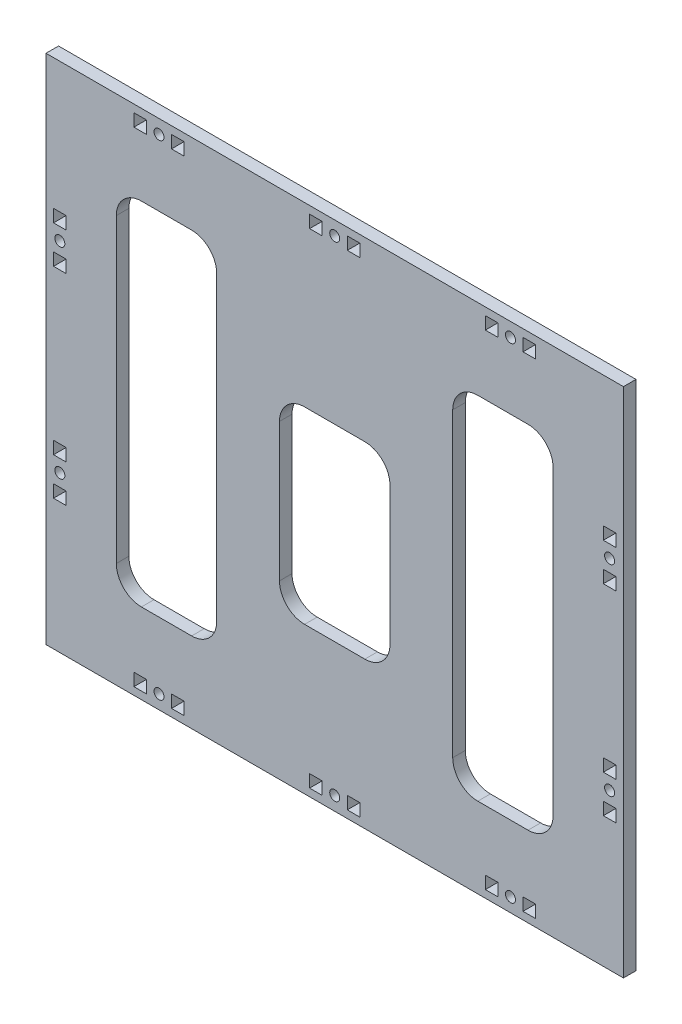
SolidWorks part; units mm, degrees
ref_plane "Plan de face" through (0, 0, 0) normal (0, 0, 1) x (1, 0, 0)
ref_plane "Plan de dessus" through (0, 0, 0) normal (0, 1, 0) x (1, 0, 0)
ref_plane "Plan de droite" through (0, 0, 0) normal (1, 0, 0) x (0, 0, -1)
sketch "Esquisse1" plane through (0, 0, 0) normal (0, 0, 1) x (1, 0, 0)
  line L0 (0, 0) -> (0, 94) construction
  line L1 (-21.3539, 94) -> (23.6911, 94) construction
  line L2 (-182, 188) -> (-182, 196)
  line L3 (-45, 188) -> (-45, 0) construction
  line L4 (-182, 196) -> (48, 196)
  line L5 (48, 196) -> (48, 188)
  line L6 (48, -8) -> (48, 0)
  line L7 (45, 0) -> (45, 188) construction
  line L8 (-182, -8) -> (48, -8)
  line L9 (-182, 0) -> (-182, -8)
  line L10 (-45, 188) -> (-45, 125.5) construction
  line L11 (-45, 125.5) -> (-89, 125.5)
  line L12 (-67, 125.5) -> (-67, 50.5) construction
  line L13 (-67, 50.5) -> (-45, 50.5)
  line L14 (-45, 50.5) -> (-45, 0) construction
  line L15 (-67, 50.5) -> (-89, 50.5)
  line L16 (-89, 50.5) -> (-89, 0) construction
  line L17 (-114, 164) -> (-154, 164)
  line L18 (-20, 164) -> (20, 164)
  line L19 (45, 0) -> (-179, 0) construction
  line L20 (-179, 0) -> (-179, 188) construction
  line L21 (-179, 188) -> (45, 188) construction
  line L22 (-20, 164) -> (-20, 24)
  line L23 (-89, 188) -> (-89, 125.5) construction
  line L24 (-20, 24) -> (20, 24)
  line L25 (-179, 0) -> (-179, 188) construction
  line L26 (-179, 0) -> (-174, 0) construction
  line L27 (-89, 125.5) -> (-89, 50.5)
  line L28 (-45, 50.5) -> (-45, 125.5)
  line L29 (20, 164) -> (20, 24)
  line L30 (-114, 164) -> (-114, 24)
  line L31 (45, 188) -> (48, 188) construction
  line L32 (48, 188) -> (48, 0)
  line L33 (48, 0) -> (45, 0) construction
  line L34 (-182, 0) -> (-179, 0) construction
  line L35 (-179, 188) -> (-182, 188) construction
  line L36 (-182, 188) -> (-182, 0)
  line L37 (-114, 24) -> (-154, 24)
  line L38 (-154, 164) -> (-154, 24)
  point P23 (0, 0)
  point P27 (0, 0)
  point P28 (-41.9171, 188)
  point P29 (-21.3539, 169.9312)
  point P30 (23.6911, 164)
  line B0 (42.5, 129) -> (42.5, 139) construction
  line B1 (40, 129) -> (40, 124)
  line B2 (40, 129) -> (45, 129)
  line B3 (45, 129) -> (45, 124)
  line B4 (40, 124) -> (45, 124)
  line B5 (40, 139) -> (40, 144)
  line B6 (40, 139) -> (45, 139)
  line B7 (45, 139) -> (45, 144)
  line B8 (40, 144) -> (45, 144)
  line B9 (42.5, 134) -> (35.5276, 134) construction
  circle B10 centre (42.5, 134) radius 2
  line B11 (42.5, 59) -> (42.5, 49) construction
  line B12 (40, 59) -> (40, 64)
  line B13 (40, 59) -> (45, 59)
  line B14 (45, 59) -> (45, 64)
  line B15 (40, 64) -> (45, 64)
  line B16 (40, 49) -> (40, 44)
  line B17 (40, 49) -> (45, 49)
  line B18 (45, 49) -> (45, 44)
  line B19 (40, 44) -> (45, 44)
  line B20 (42.5, 54) -> (35.5276, 54) construction
  circle B21 centre (42.5, 54) radius 2
  line B22 (-176.5, 129) -> (-176.5, 139) construction
  line B23 (-174, 129) -> (-174, 124)
  line B24 (-174, 129) -> (-179, 129)
  line B25 (-179, 129) -> (-179, 124)
  line B26 (-174, 124) -> (-179, 124)
  line B27 (-174, 139) -> (-174, 144)
  line B28 (-174, 139) -> (-179, 139)
  line B29 (-179, 139) -> (-179, 144)
  line B30 (-174, 144) -> (-179, 144)
  line B31 (-176.5, 134) -> (-169.5276, 134) construction
  circle B32 centre (-176.5, 134) radius 2
  line B33 (-176.5, 59) -> (-176.5, 49) construction
  line B34 (-174, 59) -> (-174, 64)
  line B35 (-174, 59) -> (-179, 59)
  line B36 (-179, 59) -> (-179, 64)
  line B37 (-174, 64) -> (-179, 64)
  line B38 (-174, 49) -> (-174, 44)
  line B39 (-174, 49) -> (-179, 49)
  line B40 (-179, 49) -> (-179, 44)
  line B41 (-174, 44) -> (-179, 44)
  line B42 (-176.5, 54) -> (-169.5276, 54) construction
  circle B43 centre (-176.5, 54) radius 2
  line B44 (-132, 190.5) -> (-142, 190.5) construction
  line B45 (-132, 193) -> (-127, 193)
  line B46 (-132, 193) -> (-132, 188)
  line B47 (-132, 188) -> (-127, 188)
  line B48 (-127, 193) -> (-127, 188)
  line B49 (-142, 193) -> (-147, 193)
  line B50 (-142, 193) -> (-142, 188)
  line B51 (-142, 188) -> (-147, 188)
  line B52 (-147, 193) -> (-147, 188)
  line B53 (-137, 190.5) -> (-137, 197.4724) construction
  circle B54 centre (-137, 190.5) radius 2
  line B55 (-2, 190.5) -> (8, 190.5) construction
  line B56 (-2, 193) -> (-7, 193)
  line B57 (-2, 193) -> (-2, 188)
  line B58 (-2, 188) -> (-7, 188)
  line B59 (-7, 193) -> (-7, 188)
  line B60 (8, 193) -> (13, 193)
  line B61 (8, 193) -> (8, 188)
  line B62 (8, 188) -> (13, 188)
  line B63 (13, 193) -> (13, 188)
  line B64 (3, 190.5) -> (3, 197.4724) construction
  circle B65 centre (3, 190.5) radius 2
  line B66 (-2, -2.5) -> (8, -2.5) construction
  line B67 (-2, -5) -> (-7, -5)
  line B68 (-2, -5) -> (-2, 0)
  line B69 (-2, 0) -> (-7, 0)
  line B70 (-7, -5) -> (-7, 0)
  line B71 (8, -5) -> (13, -5)
  line B72 (8, -5) -> (8, 0)
  line B73 (8, 0) -> (13, 0)
  line B74 (13, -5) -> (13, 0)
  line B75 (3, -2.5) -> (3, -9.4724) construction
  circle B76 centre (3, -2.5) radius 2
  line B77 (-132, -2.5) -> (-142, -2.5) construction
  line B78 (-132, -5) -> (-127, -5)
  line B79 (-132, -5) -> (-132, 0)
  line B80 (-132, 0) -> (-127, 0)
  line B81 (-127, -5) -> (-127, 0)
  line B82 (-142, -5) -> (-147, -5)
  line B83 (-142, -5) -> (-142, 0)
  line B84 (-142, 0) -> (-147, 0)
  line B85 (-147, -5) -> (-147, 0)
  line B86 (-137, -2.5) -> (-137, -9.4724) construction
  circle B87 centre (-137, -2.5) radius 2
  line B88 (-72, 190.5) -> (-62, 190.5) construction
  line B89 (-72, 193) -> (-77, 193)
  line B90 (-72, 193) -> (-72, 188)
  line B91 (-72, 188) -> (-77, 188)
  line B92 (-77, 193) -> (-77, 188)
  line B93 (-62, 193) -> (-57, 193)
  line B94 (-62, 193) -> (-62, 188)
  line B95 (-62, 188) -> (-57, 188)
  line B96 (-57, 193) -> (-57, 188)
  line B97 (-67, 190.5) -> (-67, 197.4724) construction
  circle B98 centre (-67, 190.5) radius 2
  line B99 (-72, -190.5) -> (-62, -190.5) construction
  line B100 (-72, -193) -> (-77, -193)
  line B101 (-72, -193) -> (-72, -188)
  line B102 (-72, -188) -> (-77, -188)
  line B103 (-77, -193) -> (-77, -188)
  line B104 (-62, -193) -> (-57, -193)
  line B105 (-62, -193) -> (-62, -188)
  line B106 (-62, -188) -> (-57, -188)
  line B107 (-57, -193) -> (-57, -188)
  line B108 (-67, -190.5) -> (-67, -197.4724) construction
  circle B109 centre (-67, -190.5) radius 2
  line B110 (-72, -2.5) -> (-62, -2.5) construction
  line B111 (-72, -5) -> (-77, -5)
  line B112 (-72, -5) -> (-72, 0)
  line B113 (-72, 0) -> (-77, 0)
  line B114 (-77, -5) -> (-77, 0)
  line B115 (-62, -5) -> (-57, -5)
  line B116 (-62, -5) -> (-62, 0)
  line B117 (-62, 0) -> (-57, 0)
  line B118 (-57, -5) -> (-57, 0)
  line B119 (-67, -2.5) -> (-67, -9.4724) construction
  circle B120 centre (-67, -2.5) radius 2
  dimension "D1" = 3
  dimension "D2" = 140
  dimension "D3" = 40
  dimension "D4" = 188
  dimension "D5" = 75
  dimension "D6" = 140
  dimension "D7" = 224
  dimension "D8" = 80
  dimension "D9" = 3
  dimension "D10" = 140
  dimension "D11" = 204
sketch_block_instance "Trou M4 plots 5mm-1"
sketch_block "Trou M4 plots 5mm" parameters "D2"=4, "D1"=5, "D3"=5, "D4"=10
sketch_block_instance "Trou M4 plots 5mm-3"
sketch_block_instance "Trou M4 plots 5mm-4"
sketch_block_instance "Trou M4 plots 5mm-5"
sketch_block_instance "Trou M4 plots 5mm-6"
sketch_block_instance "Trou M4 plots 5mm-7"
sketch_block_instance "Trou M4 plots 5mm-12"
sketch_block_instance "Trou M4 plots 5mm-13"
sketch_block_instance "Trou M4 plots 5mm-14"
sketch_block_instance "Trou M4 plots 5mm-15"
sketch_block_instance "Trou M4 plots 5mm-16"
extrude "Boss.-Extru.1" add sketch "Esquisse1" along normal blind 5
fillet "Congé1" radius 10 12 edges at (-20, 164, 2.5) (20, 164, 2.5) (20, 24, 2.5) (-20, 24, 2.5) (-45, 50.5, 2.5) (-45, 125.5, 2.5) (-89, 125.5, 2.5) (-89, 50.5, 2.5) (-154, 24, 2.5) (-114, 24, 2.5) (-114, 164, 2.5) (-154, 164, 2.5)
